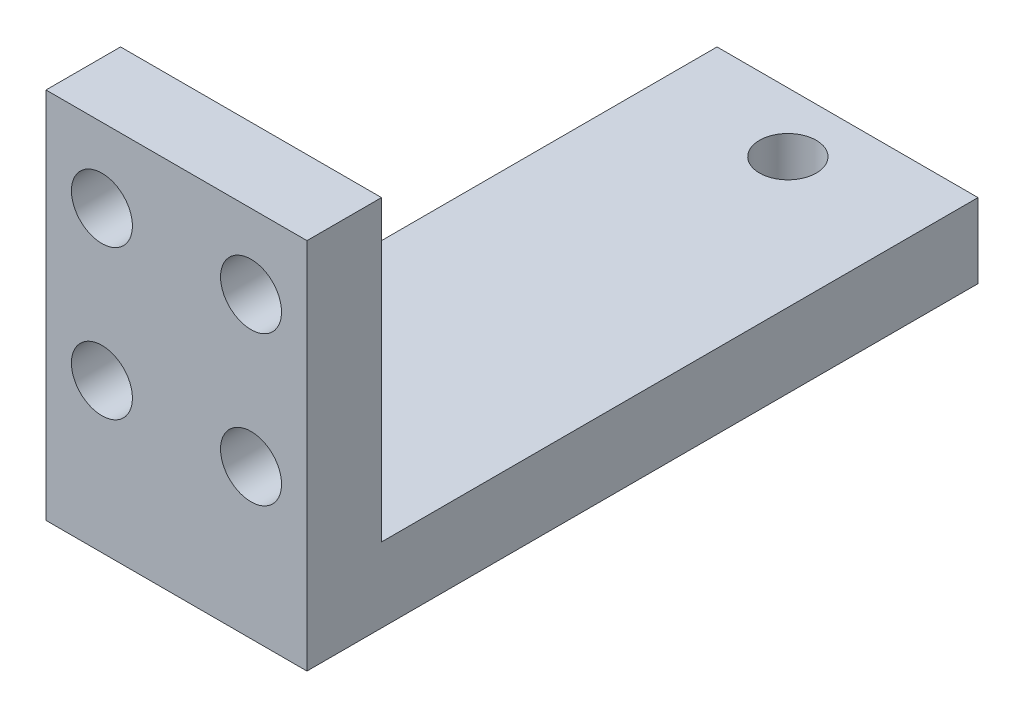
SolidWorks part; units mm, degrees
material "Delrin 2700 NC010, Low Viscosity Acetal Copolymer (SS)"
ref_plane "Front Plane" through (0, 0, 0) normal (0, 0, 1) x (1, 0, 0)
ref_plane "Top Plane" through (0, 0, 0) normal (0, 1, 0) x (1, 0, 0)
ref_plane "Right Plane" through (0, 0, 0) normal (1, 0, 0) x (0, 0, -1)
sketch "Sketch1" plane through (0, 0, 0) normal (0, 1, 0) x (1, 0, 0)
  line L1 (0, 0) -> (35, 0)
  line L2 (0, 0) -> (0, 90)
  line L3 (0, 90) -> (35, 90)
  line L4 (35, 0) -> (35, 90)
  dimension "D1" = 90
  dimension "D2" = 35
extrude "Boss-Extrude1" add sketch "Sketch1" along normal blind 10
sketch "Sketch2" plane through (0, 10, 0) normal (0, 1, 0) x (1, 0, 0)
  line L0 (35, 0) -> (35, 90) construction
  line L1 (0, 0) -> (35, 0)
  line L2 (0, 0) -> (0, 10)
  line L3 (0, 10) -> (35, 10)
  line L4 (35, 0) -> (35, 10)
  dimension "D1" = 10
extrude "Boss-Extrude2" add sketch "Sketch2" along normal blind 40
sketch "Sketch3" plane through (0, 0, -10) normal (0, 0, -1) x (-1, 0, 0)
  line L0 (-35, 50) -> (0, 50) construction
  line L1 (-27.5, 40) -> (-7.5, 40)
  line L2 (-27.5, 40) -> (-27.5, 20)
  line L3 (-27.5, 20) -> (-7.5, 20)
  line L4 (-7.5, 40) -> (-7.5, 20)
  line L5 (-35, 10) -> (0, 10) construction
  line L6 (-35, 50) -> (-35, 10) construction
  line L7 (0, 50) -> (0, 10) construction
  circle A0 centre (-27.5, 40) radius 4.0907
  circle A1 centre (-7.5, 40) radius 4.0907
  circle A2 centre (-7.5, 20) radius 4.0907
  circle A3 centre (-27.5, 20) radius 4.0907
  dimension "D1" = 10
  dimension "D2" = 10
  dimension "D3" = 7.5
  dimension "D4" = 7.5
extrude "Cut-Extrude1" cut sketch "Sketch3" against normal through all both and the other way through all contours A0 | A1 | A2 | A3
sketch "Sketch4" plane through (0, 10, 0) normal (0, 1, 0) x (1, 0, 0)
  line L0 (35, 90) -> (0, 90) construction
  circle A0 centre (17.5, 82) radius 3.81
  point P4 (17.5, 90)
  dimension "D1" = 7.62
  dimension "D2" = 8
extrude "Cut-Extrude2" cut sketch "Sketch4" against normal through all contours A0
